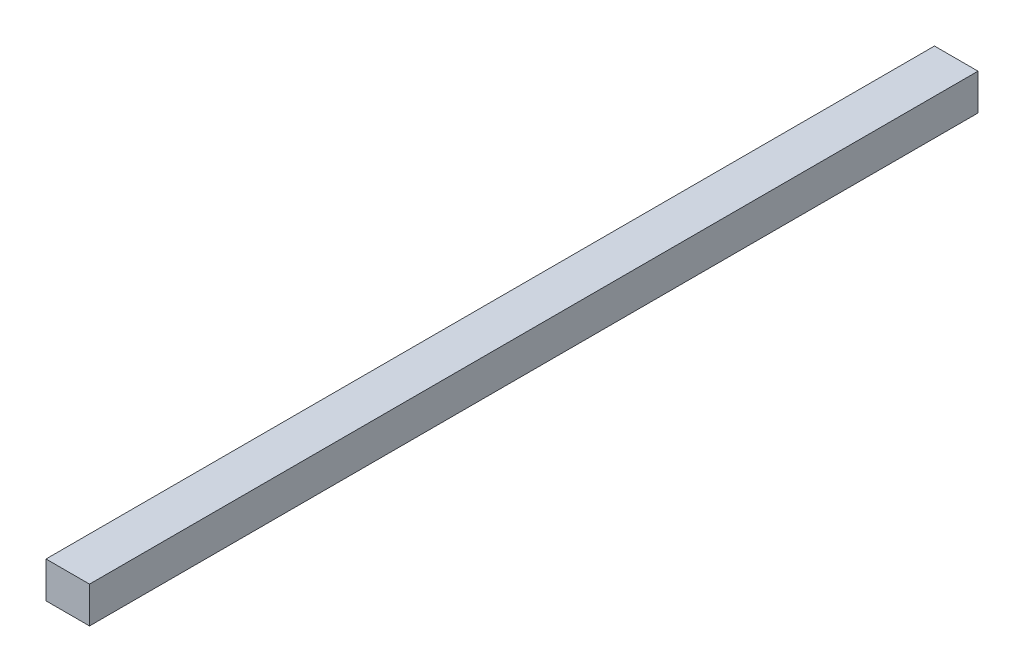
SolidWorks part; units mm, degrees
ref_plane "Front Plane" through (0, 0, 0) normal (0, 0, 1) x (1, 0, 0)
ref_plane "Top Plane" through (0, 0, 0) normal (0, 1, 0) x (1, 0, 0)
ref_plane "Right Plane" through (0, 0, 0) normal (1, 0, 0) x (0, 0, -1)
sketch "Sketch1" plane through (0, 0, 0) normal (0, 0, 1) x (1, 0, 0)
  line L1 (0, 0) -> (6, 0)
  line L2 (0, 0) -> (0, 5)
  line L3 (0, 5) -> (6, 5)
  line L4 (6, 0) -> (6, 5)
extrude "Boss-Extrude1" add sketch "Sketch1" along normal blind 122.5
